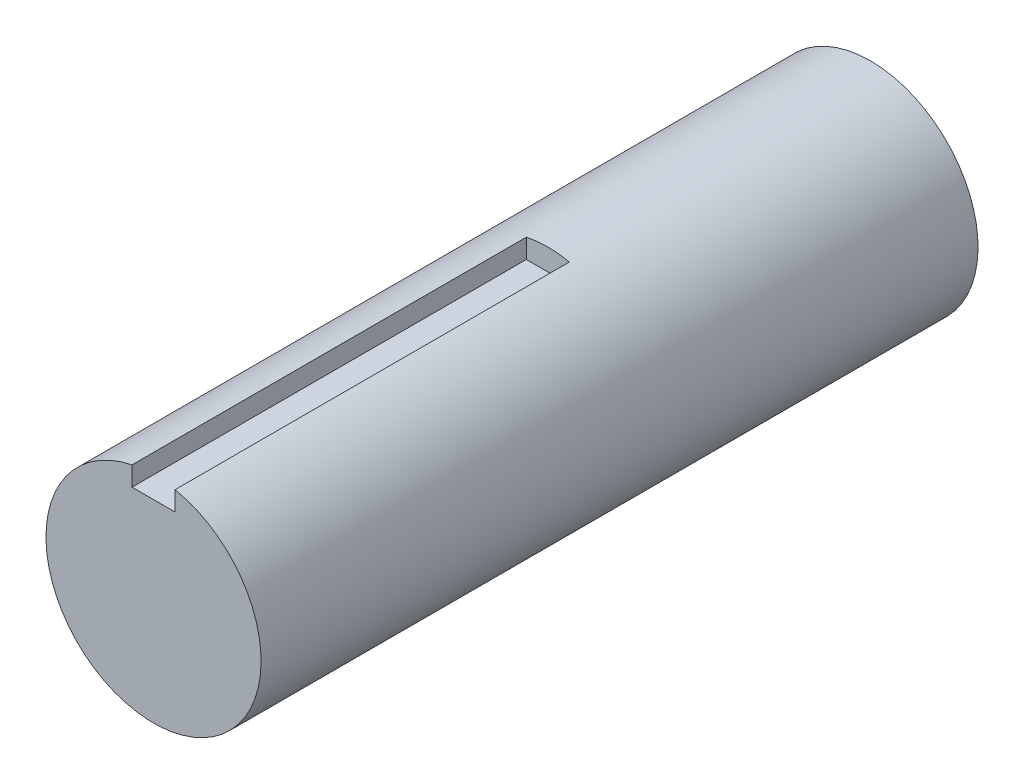
SolidWorks part; units mm, degrees
ref_plane "Front Plane" through (0, 0, 0) normal (0, 0, 1) x (1, 0, 0)
ref_plane "Top Plane" through (0, 0, 0) normal (0, 1, 0) x (1, 0, 0)
ref_plane "Right Plane" through (0, 0, 0) normal (1, 0, 0) x (0, 0, -1)
sketch "Sketch1" plane through (0, 0, 0) normal (1, 0, 0) x (0, 0, -1)
  line L1 (50, -7.5) -> (-50, -7.5)
  line L2 (50, -7.5) -> (50, 7.5)
  line L3 (50, 7.5) -> (-50, 7.5)
  line L4 (-50, -7.5) -> (-50, 7.5)
  line L5 (50, -7.5) -> (-50, 7.5) construction
  line L6 (50, 7.5) -> (-50, -7.5) construction
  point P0 (0, 0)
  dimension "D1" = 100
  dimension "D2" = 15
revolve "Revolve1" add sketch "Sketch1" angle 360 about L1
sketch "Sketch2" plane through (0, 0, 50) normal (0, 0, 1) x (1, 0, 0)
  line L1 (-3, 4.5) -> (3, 4.5)
  line L2 (-3, 4.5) -> (-3, 10.5)
  line L3 (-3, 10.5) -> (3, 10.5)
  line L4 (3, 4.5) -> (3, 10.5)
  line L5 (-3, 4.5) -> (3, 10.5) construction
  line L6 (-3, 10.5) -> (3, 4.5) construction
  circle A0 centre (0, -7.5) radius 15 construction
  point P0 (0, 7.5)
  dimension "D1" = 6
  dimension "D2" = 6
extrude "Cut-Extrude1" cut sketch "Sketch2" against normal blind 55
